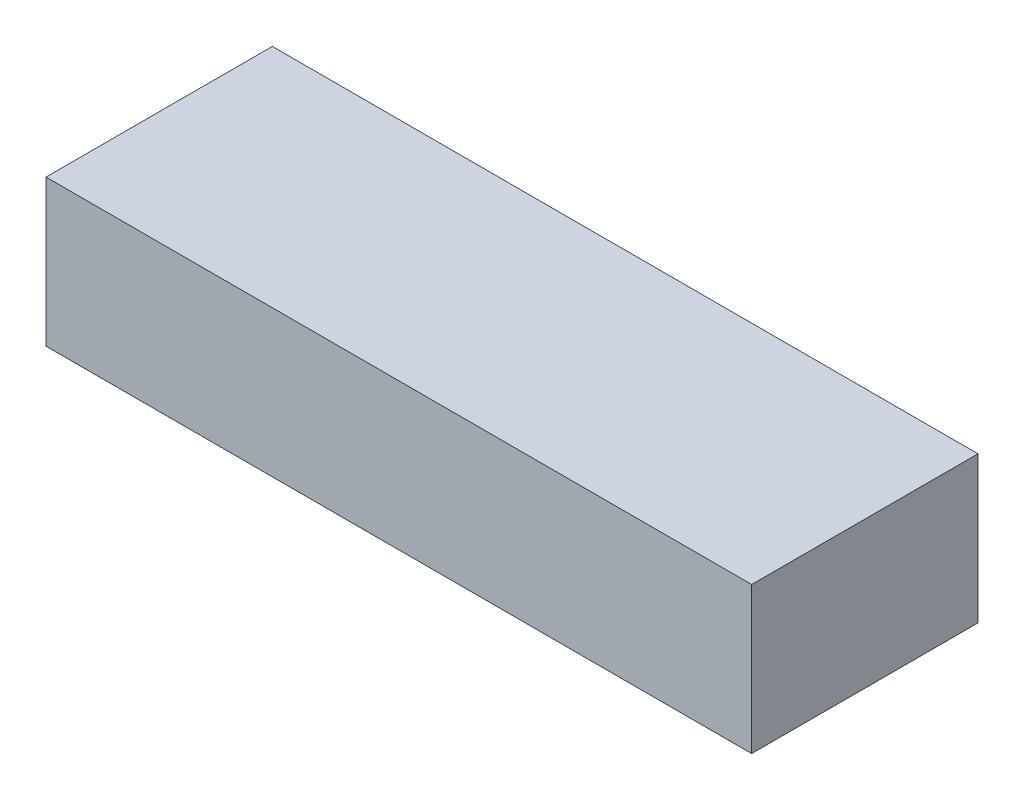
SolidWorks part; units mm, degrees
ref_plane "Front Plane" through (0, 0, 0) normal (0, 0, 1) x (1, 0, 0)
ref_plane "Top Plane" through (0, 0, 0) normal (0, 1, 0) x (1, 0, 0)
ref_plane "Right Plane" through (0, 0, 0) normal (1, 0, 0) x (0, 0, -1)
sketch "Sketch1" plane through (0, 0, 0) normal (0, 1, 0) x (1, 0, 0)
  line L1 (-53, -17) -> (53, -17)
  line L2 (-53, -17) -> (-53, 17)
  line L3 (-53, 17) -> (53, 17)
  line L4 (53, -17) -> (53, 17)
  line L5 (-53, -17) -> (53, 17) construction
  line L6 (-53, 17) -> (53, -17) construction
  point P0 (0, 0)
  dimension "D1" = 34
  dimension "D2" = 106
extrude "battery_mock" add sketch "Sketch1" along normal blind 22
